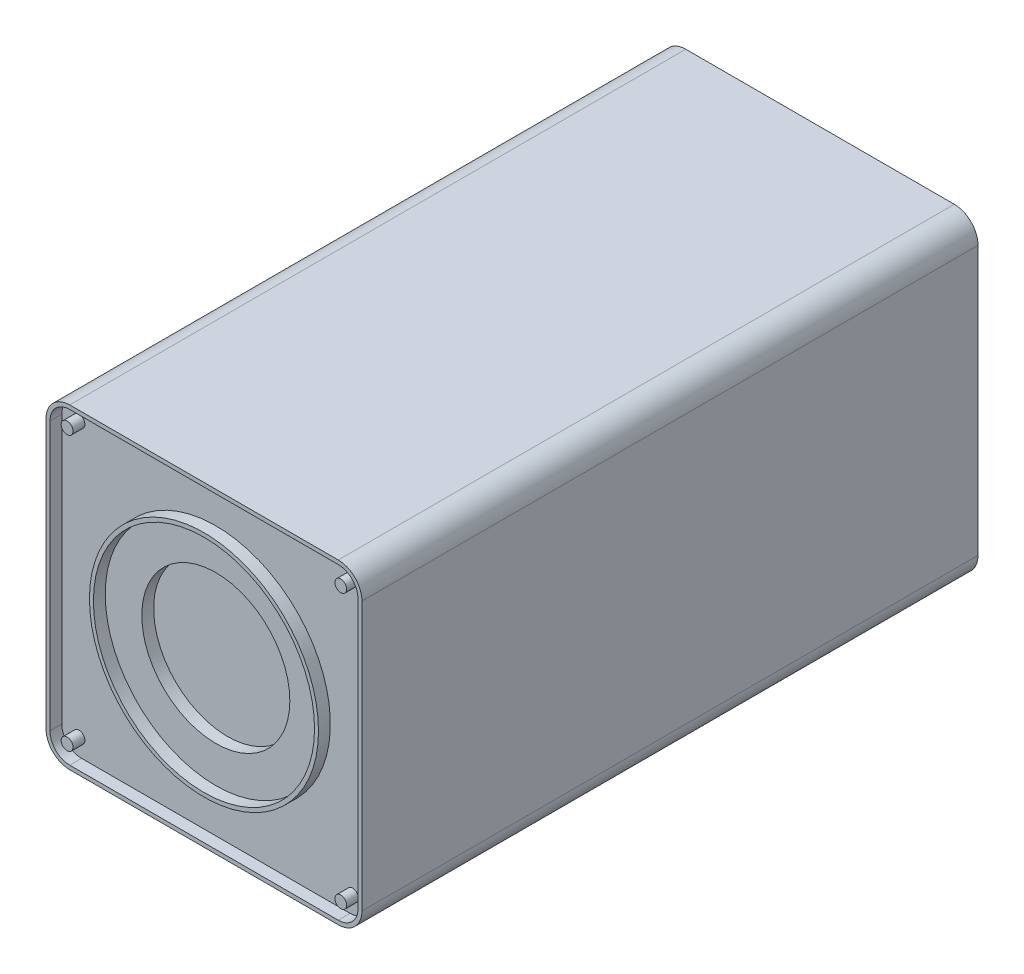
SolidWorks part; units mm, degrees
ref_plane "前视基准面" through (0, 0, 0) normal (0, 0, 1) x (1, 0, 0)
ref_plane "上视基准面" through (0, 0, 0) normal (0, 1, 0) x (1, 0, 0)
ref_plane "右视基准面" through (0, 0, 0) normal (1, 0, 0) x (0, 0, -1)
sketch "草图2" plane through (0, 0, 0) normal (0, 0, 1) x (1, 0, 0)
  line L1 (-40, -40) -> (40, -40)
  line L2 (-40, -40) -> (-40, 40)
  line L3 (-40, 40) -> (40, 40)
  line L4 (40, -40) -> (40, 40)
  line L5 (-40, -40) -> (40, 40) construction
  line L6 (-40, 40) -> (40, -40) construction
  point P0 (0, 0)
  dimension "D1" = 80
  dimension "D2" = 80
extrude "凸台-拉伸1" add sketch "草图2" along normal blind 150
fillet "圆角1" radius 6 4 edges at (-40, -40, 75) (40, -40, 75) (-40, 40, 75) (40, 40, 75)
sketch "草图3" plane through (0, 0, 150) normal (0, 0, 1) x (1, 0, 0)
  line L0 (34, 39) -> (-34, 39)
  line L1 (-39, 34) -> (-39, -34)
  line L2 (-34, -39) -> (34, -39)
  line L3 (39, -34) -> (39, 34)
  line L4 (-40, 34) -> (-40, -34)
  line L5 (-34, -40) -> (34, -40)
  line L6 (40, -34) -> (40, 34)
  line L7 (34, 40) -> (-34, 40)
  line L8 (-40, 34) -> (-40, -34)
  line L9 (-34, -40) -> (34, -40)
  line L10 (40, -34) -> (40, 34)
  line L11 (34, 40) -> (-34, 40)
  arc A0 (-34, 39) -> (-39, 34) centre (-34, 34) ccw
  arc A1 (-39, -34) -> (-34, -39) centre (-34, -34) ccw
  arc A2 (34, -39) -> (39, -34) centre (34, -34) ccw
  arc A3 (39, 34) -> (34, 39) centre (34, 34) ccw
  arc A4 (-40, -34) -> (-34, -40) centre (-34, -34) ccw
  arc A5 (34, -40) -> (40, -34) centre (34, -34) ccw
  arc A6 (40, 34) -> (34, 40) centre (34, 34) ccw
  arc A7 (-34, 40) -> (-40, 34) centre (-34, 34) ccw
  arc A8 (-40, -34) -> (-34, -40) centre (-34, -34) ccw
  arc A9 (34, -40) -> (40, -34) centre (34, -34) ccw
  arc A10 (40, 34) -> (34, 40) centre (34, 34) ccw
  arc A11 (-34, 40) -> (-40, 34) centre (-34, 34) ccw
  dimension "D1" = 0
  dimension "D2" = 1
extrude "凸台-拉伸2" add sketch "草图3" along normal blind 3
sketch "草图6" plane through (0, 0, 0) normal (0, 0, -1) x (-1, 0, 0)
  line L0 (34, 39) -> (-34, 39)
  line L1 (-39, 34) -> (-39, -34)
  line L2 (-34, -39) -> (34, -39)
  line L3 (39, -34) -> (39, 34)
  line L4 (-34, -40) -> (34, -40)
  line L5 (40, -34) -> (40, 34)
  line L6 (34, 40) -> (-34, 40)
  line L7 (-40, 34) -> (-40, -34)
  line L8 (-34, -40) -> (34, -40)
  line L9 (40, -34) -> (40, 34)
  line L10 (34, 40) -> (-34, 40)
  line L11 (-40, 34) -> (-40, -34)
  arc A0 (-34, 39) -> (-39, 34) centre (-34, 34) ccw
  arc A1 (-39, -34) -> (-34, -39) centre (-34, -34) ccw
  arc A2 (34, -39) -> (39, -34) centre (34, -34) ccw
  arc A3 (39, 34) -> (34, 39) centre (34, 34) ccw
  arc A4 (34, -40) -> (40, -34) centre (34, -34) ccw
  arc A5 (40, 34) -> (34, 40) centre (34, 34) ccw
  arc A6 (-34, 40) -> (-40, 34) centre (-34, 34) ccw
  arc A7 (-40, -34) -> (-34, -40) centre (-34, -34) ccw
  arc A8 (34, -40) -> (40, -34) centre (34, -34) ccw
  arc A9 (40, 34) -> (34, 40) centre (34, 34) ccw
  arc A10 (-34, 40) -> (-40, 34) centre (-34, 34) ccw
  arc A11 (-40, -34) -> (-34, -40) centre (-34, -34) ccw
  dimension "D1" = 0
  dimension "D2" = 1
extrude "凸台-拉伸5" add sketch "草图6" along normal blind 3
sketch "草图7" plane through (0, 0, 0) normal (0, 0, -1) x (-1, 0, 0)
  line L0 (0, -16) -> (0, 39) construction
  line L1 (34, 39) -> (-34, 39) construction
  line L4 (34, 40) -> (-34, 40) construction
  circle A0 centre (0, -16) radius 16
  circle A1 centre (0, -16) radius 17
  circle A2 centre (15, 16) radius 5.9823
  circle A3 centre (-15, 16) radius 5.9823
  dimension "D1" = 32
  dimension "D3" = 15
  dimension "D4" = 24
  dimension "D2" = 1
extrude "凸台-拉伸6" add sketch "草图7" along normal blind 3
sketch "草图8" plane through (0, 0, 150) normal (0, 0, 1) x (1, 0, 0)
  circle A0 centre (0, 0) radius 29
  circle A1 centre (0, 0) radius 28
  dimension "D1" = 58
  dimension "D2" = 1
extrude "凸台-拉伸7" add sketch "草图8" along normal blind 3
sketch "草图9" plane through (0, 0, 150) normal (0, 0, 1) x (1, 0, 0)
  line L0 (-37.5355, 37.5355) -> (37.5355, -37.5355) construction
  line L1 (37.5355, -37.5355) -> (37.5355, 37.5355) construction
  line L2 (37.5355, 37.5355) -> (-37.5355, -37.5355) construction
  line L3 (0, 39) -> (0, -39) construction
  line L4 (34, 39) -> (-34, 39) construction
  line L5 (-34, -39) -> (34, -39) construction
  line L6 (-39, 0) -> (37.5355, 0) construction
  line L7 (-39, 34) -> (-39, -34) construction
  arc A0 (-34, 39) -> (-39, 34) centre (-34, 34) ccw construction
  arc A1 (34, -39) -> (39, -34) centre (34, -34) ccw construction
  arc A2 (39, 34) -> (34, 39) centre (34, 34) ccw construction
  arc A3 (-39, -34) -> (-34, -39) centre (-34, -34) ccw construction
  circle A4 centre (-34.65, 34.65) radius 1.5
  circle A5 centre (34.65, 34.65) radius 1.5
  circle A6 centre (34.65, -34.65) radius 1.5
  circle A7 centre (-34.65, -34.65) radius 1.5
  dimension "D1" = 3
extrude "凸台-拉伸8" add sketch "草图9" along normal blind 3
sketch "草图10" plane through (0, 0, 150) normal (0, 0, 1) x (1, 0, 0)
  circle A0 centre (0, 0) radius 18.7444
extrude "切除-拉伸1" cut sketch "草图10" against normal blind 3
